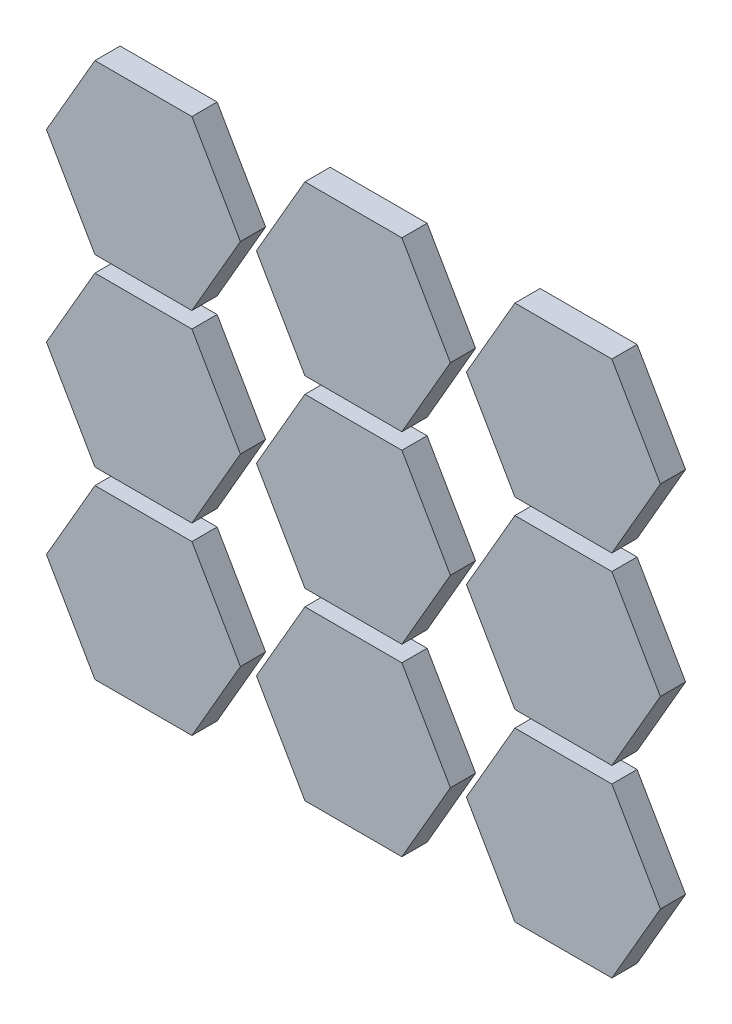
SolidWorks part; units mm, degrees
ref_plane "Front Plane" through (0, 0, 0) normal (0, 0, 1) x (1, 0, 0)
ref_plane "Top Plane" through (0, 0, 0) normal (0, 1, 0) x (1, 0, 0)
ref_plane "Right Plane" through (0, 0, 0) normal (1, 0, 0) x (0, 0, -1)
sketch "Sketch1" plane through (0, 0, 0) normal (0, 0, 1) x (1, 0, 0)
  line L0 (30.7735, -10) -> (36.547, 0)
  line L1 (5.7735, -10) -> (11.547, 0)
  line L2 (11.547, 0) -> (5.7735, 10)
  line L3 (5.7735, 10) -> (-5.7735, 10)
  line L4 (-5.7735, 10) -> (-11.547, 0)
  line L5 (-11.547, 0) -> (-5.7735, -10)
  line L6 (-5.7735, -10) -> (5.7735, -10)
  line L7 (36.547, 0) -> (30.7735, 10)
  line L8 (30.7735, 10) -> (19.2265, 10)
  line L9 (19.2265, 10) -> (13.453, 0)
  line L10 (13.453, 0) -> (19.2265, -10)
  line L11 (19.2265, -10) -> (30.7735, -10)
  line L12 (55.7735, -10) -> (61.547, 0)
  line L13 (61.547, 0) -> (55.7735, 10)
  line L14 (55.7735, 10) -> (44.2265, 10)
  line L15 (44.2265, 10) -> (38.453, 0)
  line L16 (38.453, 0) -> (44.2265, -10)
  line L17 (44.2265, -10) -> (55.7735, -10)
  line L18 (30.7735, 11.91) -> (36.547, 21.91)
  line L19 (5.7735, 11.91) -> (11.547, 21.91)
  line L20 (11.547, 21.91) -> (5.7735, 31.91)
  line L21 (5.7735, 31.91) -> (-5.7735, 31.91)
  line L22 (-5.7735, 31.91) -> (-11.547, 21.91)
  line L23 (-11.547, 21.91) -> (-5.7735, 11.91)
  line L24 (-5.7735, 11.91) -> (5.7735, 11.91)
  line L25 (36.547, 21.91) -> (30.7735, 31.91)
  line L26 (30.7735, 31.91) -> (19.2265, 31.91)
  line L27 (19.2265, 31.91) -> (13.453, 21.91)
  line L28 (13.453, 21.91) -> (19.2265, 11.91)
  line L29 (19.2265, 11.91) -> (30.7735, 11.91)
  line L30 (55.7735, 11.91) -> (61.547, 21.91)
  line L31 (61.547, 21.91) -> (55.7735, 31.91)
  line L32 (55.7735, 31.91) -> (44.2265, 31.91)
  line L33 (44.2265, 31.91) -> (38.453, 21.91)
  line L34 (38.453, 21.91) -> (44.2265, 11.91)
  line L35 (44.2265, 11.91) -> (55.7735, 11.91)
  line L36 (30.7735, 33.82) -> (36.547, 43.82)
  line L37 (5.7735, 33.82) -> (11.547, 43.82)
  line L38 (11.547, 43.82) -> (5.7735, 53.82)
  line L39 (5.7735, 53.82) -> (-5.7735, 53.82)
  line L40 (-5.7735, 53.82) -> (-11.547, 43.82)
  line L41 (-11.547, 43.82) -> (-5.7735, 33.82)
  line L42 (-5.7735, 33.82) -> (5.7735, 33.82)
  line L43 (36.547, 43.82) -> (30.7735, 53.82)
  line L44 (30.7735, 53.82) -> (19.2265, 53.82)
  line L45 (19.2265, 53.82) -> (13.453, 43.82)
  line L46 (13.453, 43.82) -> (19.2265, 33.82)
  line L47 (19.2265, 33.82) -> (30.7735, 33.82)
  line L48 (55.7735, 33.82) -> (61.547, 43.82)
  line L49 (61.547, 43.82) -> (55.7735, 53.82)
  line L50 (55.7735, 53.82) -> (44.2265, 53.82)
  line L51 (44.2265, 53.82) -> (38.453, 43.82)
  line L52 (38.453, 43.82) -> (44.2265, 33.82)
  line L53 (44.2265, 33.82) -> (55.7735, 33.82)
  dimension "D1" = 20
  dimension "D2" = 3
  dimension "D4" = 1.906
  dimension "D5" = 1.91
  dimension "D3" = 3
extrude "Boss-Extrude1" add sketch "Sketch1" along normal blind 3
